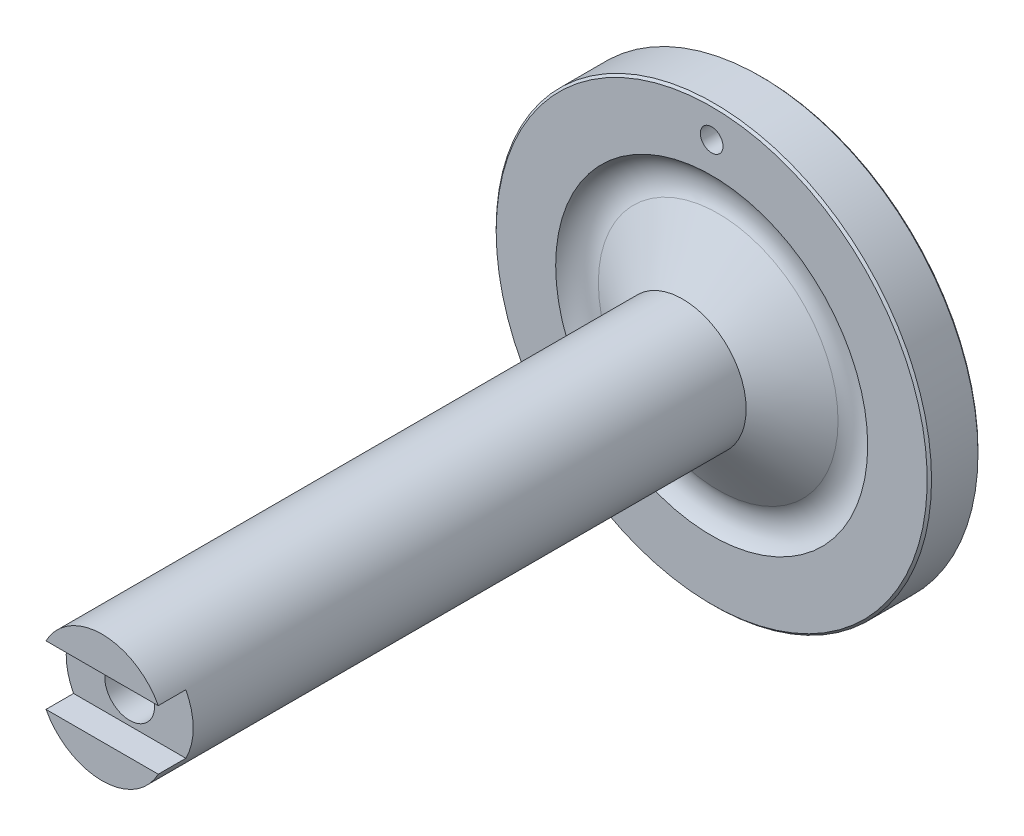
SolidWorks part; units mm, degrees
material "Malleable Cast Iron"
ref_plane "Front Plane" through (0, 0, 0) normal (0, 0, 1) x (1, 0, 0)
ref_plane "Top Plane" through (0, 0, 0) normal (0, 1, 0) x (1, 0, 0)
ref_plane "Right Plane" through (0, 0, 0) normal (1, 0, 0) x (0, 0, -1)
sketch "Sketch1" plane through (0, 0, 0) normal (1, 0, 0) x (0, 0, -1)
  line L0 (0, 0) -> (178.9077, 0) construction
  line L1 (0, 8.7376) -> (0, 22.225)
  line L2 (0, 22.225) -> (203.2, 22.225)
  line L3 (203.2, 22.225) -> (215.6446, 41.95)
  line L4 (213.36, 54.61) -> (213.36, 76.2)
  line L5 (213.36, 76.2) -> (231.14, 76.2)
  line L6 (231.14, 76.2) -> (231.14, 54.61)
  line L7 (231.14, 54.61) -> (217.1507, 32.4366)
  line L8 (223.2152, 15.875) -> (223.2152, 8.7376)
  line L9 (223.2152, 8.7376) -> (0, 8.7376)
  line L10 (0, 22.225) -> (0, 0) construction
  line L11 (218.4712, 20.619) -> (223.2152, 15.875)
  arc A0 (215.6446, 41.95) -> (213.36, 54.61) centre (207.5889, 47.0324) ccw
  arc A2 (217.1507, 32.4366) -> (218.4712, 20.619) centre (225.2064, 27.3542) ccw
  dimension "D1" = 152.4
  dimension "D11" = 9.525
  dimension "D13" = 45
  dimension "D14" = 9.525
  dimension "D2" = 44.45
  dimension "D3" = 31.75
  dimension "D4" = 17.4752
  dimension "D5" = 10.16
  dimension "D6" = 17.78
  dimension "D7" = 21.59
  dimension "D8" = 21.59
  dimension "D9" = 203.2
  dimension "D10" = 6.35
  dimension "D12" = 7.9248
revolve "Revolve1" add sketch "Sketch1" angle 360 about L0
chamfer "Chamfer1" distance 0.762 angle 45 2 edges at (76.2, 0, -231.14) (76.2, 0, -213.36)
sketch "Sketch2" plane through (0, 0, 0) normal (1, 0, 0) x (0, 0, -1)
  line L0 (54.7462, 0) -> (-54.7462, 0) construction
  line L1 (9.652, -10.3886) -> (0, -10.3886)
  line L2 (9.652, -10.3886) -> (9.652, 10.3886)
  line L3 (9.652, 10.3886) -> (0, 10.3886)
  line L4 (0, -10.3886) -> (0, 10.3886)
  line L5 (9.652, -10.3886) -> (0, 10.3886) construction
  line L6 (9.652, 10.3886) -> (0, -10.3886) construction
  line L7 (0, 54.9142) -> (0, -54.9142) construction
  point P0 (4.826, 0)
  dimension "D1" = 9.652
  dimension "D2" = 20.7772
extrude "Cut-Extrude1" cut sketch "Sketch2" against normal through all both and the other way through all
sketch "Sketch3" plane through (0, 0, -231.14) normal (0, 0, -1) x (-1, 0, 0)
  line L0 (0, 76.2) -> (0, 54.61) construction
  circle A0 centre (0, 65.405) radius 3.9624
  circle A1 centre (0, 0) radius 76.2 construction
  circle A2 centre (0, 0) radius 54.61 construction
  dimension "D1" = 7.9248
extrude "Cut-Extrude2" cut sketch "Sketch3" against normal through all
